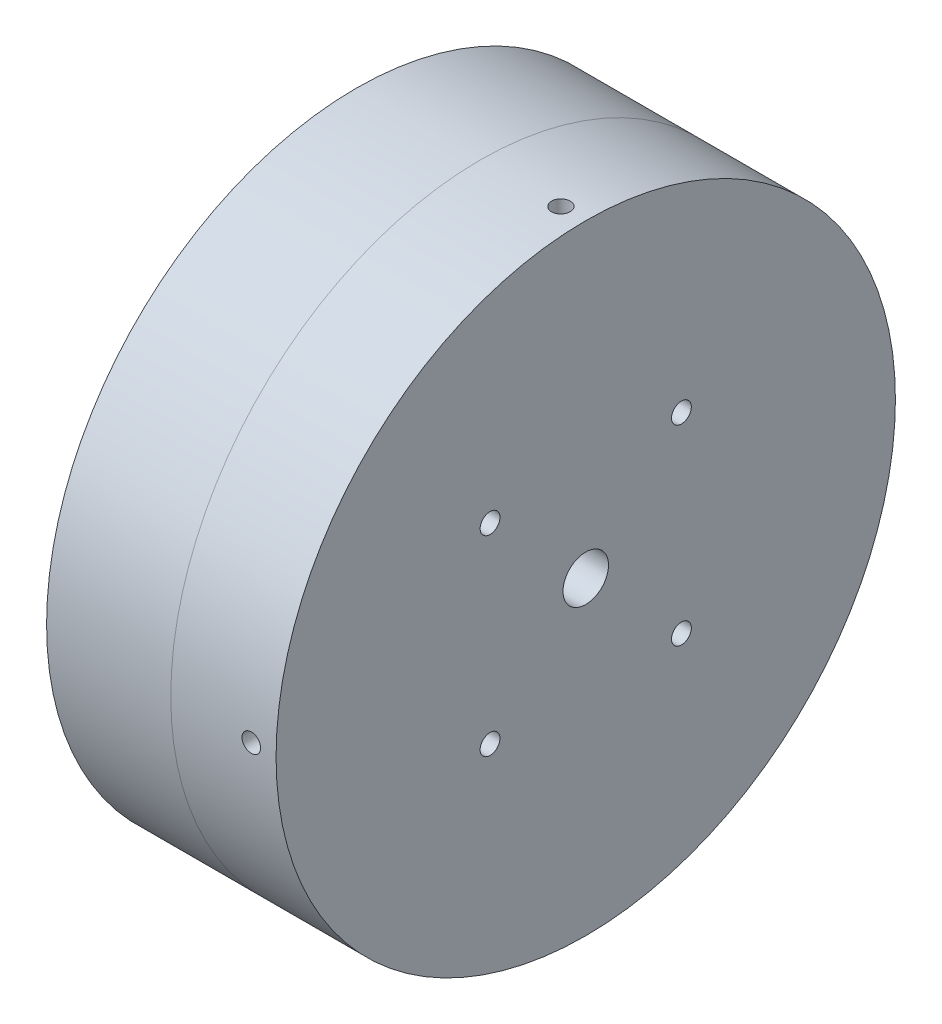
SolidWorks part; units mm, degrees
ref_plane "Plane1" through (0, 0, 0) normal (0, 0, 1) x (1, 0, 0)
ref_plane "Plane2" through (0, 0, 0) normal (0, 1, 0) x (1, 0, 0)
ref_plane "Plane3" through (0, 0, 0) normal (1, 0, 0) x (0, 0, -1)
other "Configuration Table"
sketch "HoldingSke" plane through (0, 0, 0) normal (0, 1, 0) x (1, 0, 0)
  line L0 (0, 0) -> (0.4377, -0.3673)
  line L1 (-15, 0) -> (100, 0) construction
  line L2 (0, 0) -> (-2.1039, 2.3779)
  line L3 (0, 0) -> (-11.863, 4.5341)
  line L4 (0, 0) -> (6.6156, 5.5511)
  line L5 (0, 0) -> (-23.7986, -8.8762)
  line L6 (0, 0) -> (-10.5278, -7.1032)
  line L7 (-2.1039, 2.3779) -> (3.3635, 27.1825)
  line L8 (-76.2, 4.1279) -> (-54.61, 4.1279)
  line L9 (-71.009, 38.7566) -> (-53.1078, 45.2721)
  line L10 (-76.2, 71.12) -> (104.1128, 71.12)
  line L11 (0, 0) -> (-10, 0)
  line L12 (-76.2, 101.6) -> (-76.147, 101.6)
  line L13 (24.9733, 27.94) -> (52.9518, 28.4284)
  line L14 (24.9733, 27.94) -> (24.9743, 27.94)
  line L15 (24.9733, 27.94) -> (100.4006, 29.5858)
  circle A0 centre (0, 0) radius 38.1
  circle A1 centre (0, 0) radius 12.7
  circle A2 centre (0, 0) radius 12.7
  dimension "MHD" = 25.4
  dimension "Hub_dia" = 25.4
  dimension "Diameter" = 76.2
  dimension "Num_teeth" = 40
  dimension "Pitch" = 0.5714
  dimension "Overall_len" = 25.4
  dimension "Show_teeth" = 40
  dimension "Thickness" = 12.7
  dimension "OAL" = 25.4001
  dimension "T_dim" = 21.59
  dimension "Ap" = 20
  dimension "H" = 19.05
  dimension "Pitch_radius" = 180.3128
  dimension "Width" = 10
  dimension "Backlash" = 0.053
  dimension "Addendum_fac" = 1
  dimension "Dedendum_fac" = 1.25
  dimension "Clearance_fac" = 0.25
  dimension "Dedendum_add" = 0.001
  dimension "Module" = 1.75
sketch "BasProSke" plane through (0, 0, 0) normal (0, 1, 0) x (1, 0, 0)
  line L0 (-10, 0) -> (60, 0) construction
  line L1 (0, 33.25) -> (0, 38.1)
  line L2 (0, 33.25) -> (10, 33.25)
  line L3 (10, 33.25) -> (10, 38.1)
  line L4 (10, 38.1) -> (0, 38.1)
  dimension "Diameter" = 76.2
  dimension "Thickness" = 10
  dimension "Inside_diameter" = 66.5
revolve "Base-Revolve" add sketch "BasProSke" angle 360 about L0
sketch "TooCutSke" plane through (0, 0, 0) normal (1, 0, 0) x (0, 0, -1)
  line L3 (1.5066, 34.9676) -> (1.5066, 53.6633) construction
  line L4 (0, 0) -> (0, 59.563) construction
  line L5 (0, 0) -> (-5.3609, 68.1169) construction
  line L6 (-14.7662, 28.5297) -> (35.4037, 32.4782) construction
  circle A0 centre (0, 0) radius 35 construction
  circle A1 centre (0, 0) radius 37.1885 construction
  circle A2 centre (0, 0) radius 29.6003 construction
  circle A3 centre (0, 0) radius 33.2246 construction
  arc A4 (2.1108, 33.1575) -> (0.443, 37.1859) centre (-14.7662, 28.5297) ccw
  arc A5 (2.1108, 33.1575) -> (-2.1108, 33.1575) centre (0, 0) ccw
  arc A6 (0.443, 37.1859) -> (-0.443, 37.1859) centre (0, 0) ccw
  arc A7 (-0.443, 37.1859) -> (-2.1108, 33.1575) centre (14.7662, 28.5297) ccw
  dimension "Pitch_dia" = 70
  dimension "Base_dia" = 59.2006
  dimension "Root_dia" = 74.377
  dimension "Overcut_dia" = 66.4492
  dimension "Flank_rad" = 17.5
  dimension "Half_ang" = 4.5
  dimension "Half_CT" = 1.5066
extrude "ToothCut" cut sketch "TooCutSke" along normal through all
fillet "Breaks" [suppressed] radius 0.175
fillet "RootFillets" [suppressed] radius 0.4385
pattern_circular "TeethCuts" count 40 over 360 about axis through (0, 0, 0) along (1, 0, 0) of "RootFillets", "Breaks", "ToothCut"
sketch "Sketch4" plane through (10, 0, 0) normal (1, 0, 0) x (0, 0, -1)
  circle A0 centre (0, 0) radius 50
  circle A1 centre (0, 0) radius 38.1
  dimension "D1" = 100
extrude "Boss-Extrude4" add sketch "Sketch4" against normal blind 10
sketch "Sketch5" plane through (0, 0, 0) normal (-1, 0, 0) x (0, 0, 1)
  circle A0 centre (0, 0) radius 40.7
  circle A1 centre (0, 0) radius 45
  circle A2 centre (0, 0) radius 50
  dimension "D1" = 81.4
  dimension "D2" = 90
  dimension "D3" = 100
sketch "Sketch12" plane through (10, 0, 0) normal (1, 0, 0) x (0, 0, -1)
  circle A0 centre (0, 0) radius 50
  dimension "D1" = 100
extrude "Boss-Extrude6" add sketch "Sketch12" along normal blind 7
sketch "Sketch13" plane through (10, 0, 0) normal (-1, 0, 0) x (0, 0, 1)
  circle A0 centre (0, 0) radius 37.1885
  dimension "D1" = 74.377
extrude "Cut-Extrude1" cut sketch "Sketch13" along normal blind 0.5
sketch "Sketch16" plane through (17, 0, 0) normal (1, 0, 0) x (0, 0, -1)
  circle A0 centre (0, 0) radius 3.67
  dimension "D1" = 7.34
extrude "Cut-Extrude2" cut sketch "Sketch16" against normal blind 20.5
ref_plane "Plane4" through (0, 32.2093, 8.2535) normal (0, 0.2482, -0.9687) x (-1, 0, 0)
extrude "Boss-Extrude7" add sketch "Sketch5" along normal blind 20.05 separate body contours A2 A0
ref_plane "Plane5" through (0, 50, 0) normal (0, 1, 0) x (1, 0, 0)
sketch "Sketch24" plane through (0, 50, 0) normal (0, 1, 0) x (1, 0, 0)
  circle A0 centre (13.0003, 0) radius 1.5
  dimension "D1" = 3
extrude "Cut-Extrude4" cut sketch "Sketch24" against normal blind 10
mirror "Mirror1" about plane through (0, 0, 0) normal (0, 1, 0) of "Cut-Extrude4"
pattern_circular "CirPattern1" count 2 every 90 about axis through (17, 0, 0) along (1, 0, 0) of "Mirror1", "Cut-Extrude4"
sketch "Sketch25" plane through (10, 0, 0) normal (-1, 0, 0) x (0, 0, 1)
  line L0 (0, 0) -> (-29.9489, 0) construction
  line L1 (-15.45, 15.45) -> (15.45, 15.45) construction
  line L2 (-15.45, 15.45) -> (-15.45, -15.45) construction
  line L3 (-15.45, -15.45) -> (15.45, -15.45) construction
  line L4 (15.45, 15.45) -> (15.45, -15.45) construction
  line L5 (-15.45, 15.45) -> (15.45, -15.45) construction
  line L6 (-15.45, -15.45) -> (15.45, 15.45) construction
  line L7 (0, 15.45) -> (0, -15.45) construction
  circle A0 centre (-15.45, 15.45) radius 1.6
  circle A1 centre (-15.45, -15.45) radius 1.6
  circle A2 centre (15.45, -15.45) radius 1.6
  circle A3 centre (15.45, 15.45) radius 1.6
  point P0 (0, 0)
  dimension "D3" = 3.2
  dimension "D1" = 30.9
  dimension "D2" = 30.9
extrude "Cut-Extrude5" cut sketch "Sketch25" against normal through all
equation "' \"Module@HoldingSke\" = 6.35"
equation "' \"Num_teeth@HoldingSke\" = 24"
equation "' \"Ap@HoldingSke\" =  14.5"
equation "' \"Ap@HoldingSke\" = 14.5"
equation "' \"Width@HoldingSke\" = 12"
equation "' \"Diameter@HoldingSke\" = 8 * 25.4"
equation "' \"Show_teeth@HoldingSke\" = 100"
equation "' \"Backlash@HoldingSke\" = 0.009 * 25.4"
equation "' \"Addendum_fac@HoldingSke\" = 1.0"
equation "' \"Dedendum_fac@HoldingSke\" = 1.25"
equation "' \"Dedendum_add@HoldingSke\" = 0.00005 * 25.4"
equation "' \"Clearance_fac@HoldingSke\" = 0.25"
equation "\"Pitch@HoldingSke\" = 1 / \"Module@HoldingSke\" "
equation "\"Overcut_dia@TooCutSke\" = (\"Num_teeth@HoldingSke\" - 2 * \"Addendum_fac@HoldingSke\") / \"Pitch@HoldingSke\" - 0.002 * 25.4"
equation "\"Pitch_dia@TooCutSke\" = \"Num_teeth@HoldingSke\" / \"Pitch@HoldingSke\""
equation "\"Base_dia@TooCutSke\" = \"Num_teeth@HoldingSke\" / \"Pitch@HoldingSke\" * cos((\"Ap@HoldingSke\"  * 3.14159265 / 180)) * 0.90"
equation "\"Root_dia@TooCutSke\" = \"Num_teeth@HoldingSke\"  / \"Pitch@HoldingSke\" + 2 *  \"Dedendum_fac@HoldingSke\"/ \"Pitch@HoldingSke\" + \"Dedendum_add@HoldingSke\" * 2"
equation "\"Half_ang@TooCutSke\" = 180 / \"Num_teeth@HoldingSke\""
equation "\"Half_CT@TooCutSke\" = \"Num_teeth@HoldingSke\" / \"Pitch@HoldingSke\" * sin((3.14159265 / 2 / \"Num_teeth@HoldingSke\")) / 2 + 10 * \"Backlash@HoldingSke\" / 4"
equation "\"Flank_rad@TooCutSke\" = \"Num_teeth@HoldingSke\" / \"Pitch@HoldingSke\" / 4"
equation "\"Radius@RootFillets\"= \"Clearance_fac@HoldingSke\" / \"Pitch@HoldingSke\" + \"Dedendum_add@HoldingSke\""
equation "\"Break_rad@Breaks\" = 0.02 / \"Pitch@HoldingSke\" * 5"
equation "\"Num_teeth@TeethCuts\" = int( \"Show_teeth@HoldingSke\" ) + 1"
equation "\"Num_teeth@TeethCuts\" = ((sgn( \"Num_teeth@TeethCuts\" - \"Num_teeth@HoldingSke\" )-1)*( \"Num_teeth@TeethCuts\" - \"Num_teeth@HoldingSke\" ))/-2+ \"Num_teeth@HoldingSke\""
equation "\"Num_teeth@TeethCuts\" = ((sgn( \"Num_teeth@TeethCuts\" - 2.0)+1)*( \"Num_teeth@TeethCuts\" - 2.0))/2 +2.0"
equation "\"Angle@TeethCuts\" = 360.0 / \"Num_teeth@HoldingSke\""
equation "\"Diameter@BasProSke\" = \"Num_teeth@HoldingSke\"  / \"Pitch@HoldingSke\" + 2 *  \"Dedendum_fac@HoldingSke\"/ \"Pitch@HoldingSke\" + \"Dedendum_add@HoldingSke\" * 2 + 0.002 * 25.4"
equation "\"Diameter@BasProSke\" = ((sgn( \"Diameter@BasProSke\"  - \"Diameter@HoldingSke\" )+1)*( \"Diameter@BasProSke\"  - \"Diameter@HoldingSke\" ))/2 + \"Diameter@HoldingSke\""
equation "\"Inside_diameter@BasProSke\" =  (\"Num_teeth@HoldingSke\" - 2 * \"Addendum_fac@HoldingSke\") / \"Pitch@HoldingSke\" "
equation "\"Thickness@BasProSke\"  = \"Width@HoldingSke\""
